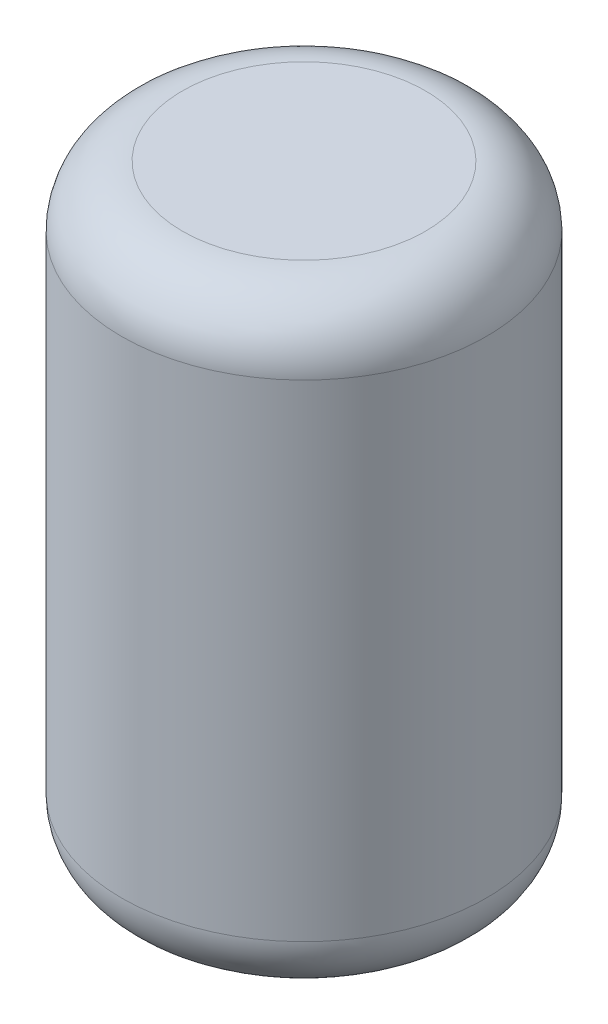
SolidWorks part; units mm, degrees
ref_plane "前基準面" through (0, 0, 0) normal (0, 0, 1) x (1, 0, 0)
ref_plane "上基準面" through (0, 0, 0) normal (0, 1, 0) x (1, 0, 0)
ref_plane "右基準面" through (0, 0, 0) normal (1, 0, 0) x (0, 0, -1)
sketch "草圖2" plane through (0, 0, 0) normal (0, 1, 0) x (1, 0, 0)
  circle A0 centre (0, 0) radius 30
  dimension "D1" = 60
extrude "伸長1" add sketch "草圖2" along normal blind 100
fillet "圓角1" radius 10 2 edges at (0, 0, 30) (0, 100, 30)
